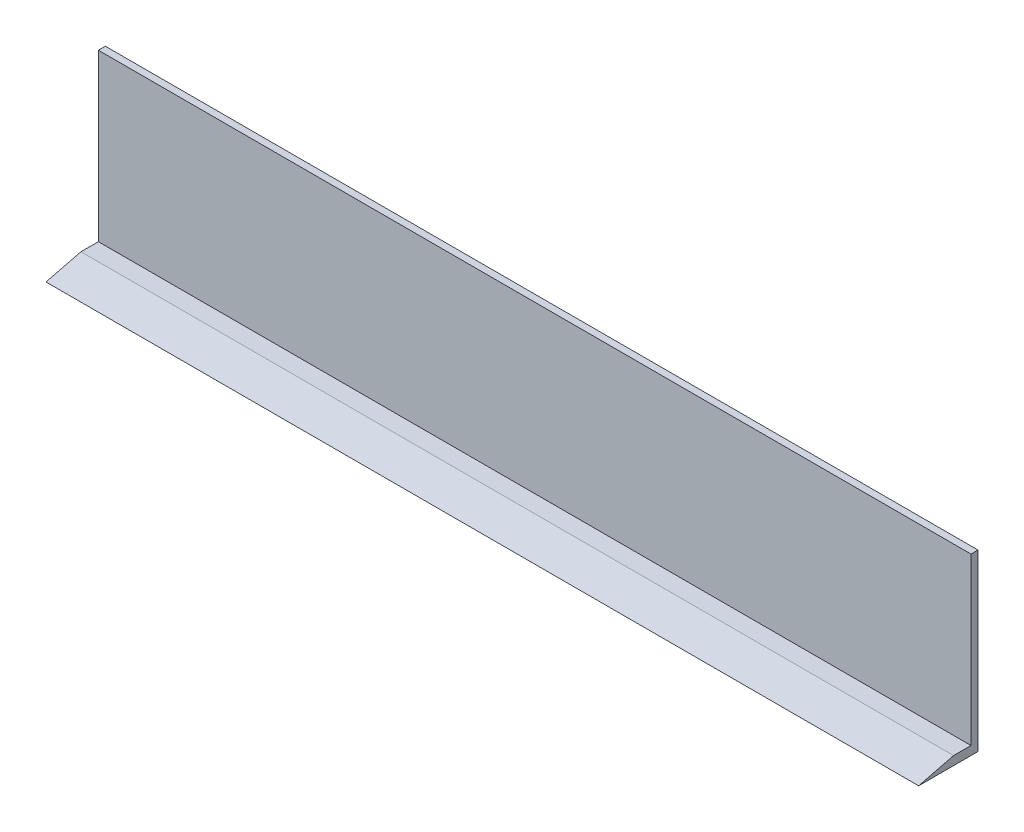
SolidWorks part; units mm, degrees
ref_plane "Plan de face" through (0, 0, 0) normal (0, 0, 1) x (1, 0, 0)
ref_plane "Plan de dessus" through (0, 0, 0) normal (0, 1, 0) x (1, 0, 0)
ref_plane "Plan de droite" through (0, 0, 0) normal (1, 0, 0) x (0, 0, -1)
sketch "Esquisse1" plane through (0, 0, 0) normal (0, 0, 1) x (1, 0, 0)
  line L1 (0, 0) -> (-250, 0)
  line L2 (0, 0) -> (0, 50)
  line L3 (0, 50) -> (-250, 50)
  line L4 (-250, 0) -> (-250, 50)
  dimension "D1" = 250
  dimension "D2" = 50
extrude "Boss.-Extru.1" add sketch "Esquisse1" along normal blind 2
sketch "Esquisse2" plane through (0, 0, 0) normal (1, 0, 0) x (0, 0, -1)
  line L0 (-2, 0) -> (-17, 0)
  line L1 (-2, 2.5) -> (-7, 2.5)
  line L2 (-2, 0) -> (-2, 50) construction
  line L3 (-2, 2.5) -> (-2, 0)
  line L4 (-17, 0) -> (-7, 2.5)
  dimension "D1" = 15
  dimension "D2" = 5
extrude "Boss.-Extru.2" add sketch "Esquisse2" against normal blind 250
